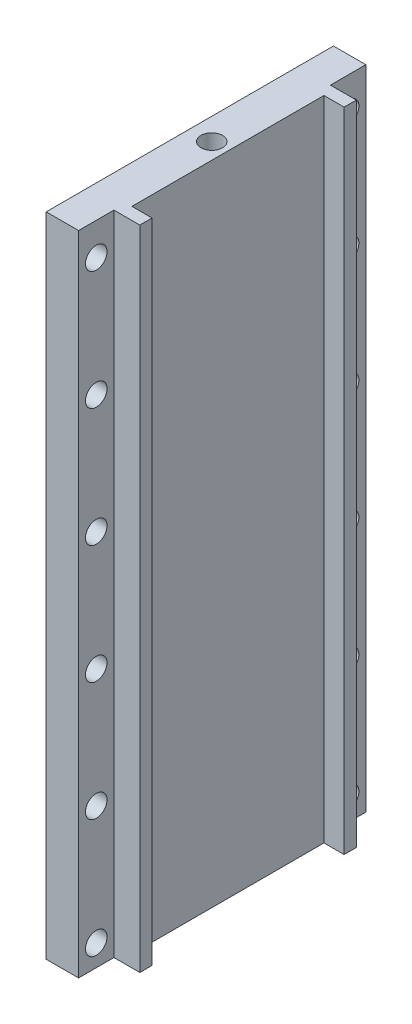
SolidWorks part; units mm, degrees
ref_plane "Front Plane" through (0, 0, 0) normal (0, 0, 1) x (1, 0, 0)
ref_plane "Top Plane" through (0, 0, 0) normal (0, 1, 0) x (1, 0, 0)
ref_plane "Right Plane" through (0, 0, 0) normal (1, 0, 0) x (0, 0, -1)
sketch "Sketch2" plane through (0, 0, 0) normal (0, 1, 0) x (1, 0, 0)
  line L0 (0, 0) -> (0, 133.12)
  line L1 (0, 133.12) -> (15, 133.12)
  line L2 (15, 133.12) -> (15, 116.725)
  line L3 (15, 116.725) -> (27, 116.725)
  line L4 (27, 116.725) -> (27, 111.06)
  line L5 (27, 111.06) -> (17.665, 111.06)
  line L6 (17.665, 111.06) -> (17.665, 22.06)
  line L7 (17.665, 22.06) -> (27, 22.06)
  line L8 (0, 0) -> (15, 0)
  line L9 (15, 0) -> (15, 16.395)
  line L10 (15, 16.395) -> (27, 16.395)
  line L11 (27, 16.395) -> (27, 22.06)
  dimension "D1" = 89
  dimension "D2" = 100.33
  dimension "D3" = 9.335
  dimension "D4" = 15
  dimension "D5" = 133.12
  dimension "D6" = 12
extrude "Boss-Extrude1" add sketch "Sketch2" along normal blind 300
sketch "Sketch3" plane through (15, 0, 0) normal (1, 0, 0) x (0, 0, -1)
  line L0 (0, 300) -> (16.395, 300) construction
  line L1 (16.395, 300) -> (116.725, 300) construction
  line L2 (66.56, 300) -> (66.56, 265.5045) construction
  circle A0 centre (8.1975, 285) radius 5
  circle A1 centre (8.1975, 230) radius 5
  circle A2 centre (8.1975, 175) radius 5
  circle A3 centre (8.1975, 120) radius 5
  circle A4 centre (8.1975, 65) radius 5
  circle A5 centre (8.1975, 10) radius 5
  circle A6 centre (124.9225, 10) radius 5
  circle A7 centre (124.9225, 65) radius 5
  circle A8 centre (124.9225, 120) radius 5
  circle A9 centre (124.9225, 175) radius 5
  circle A10 centre (124.9225, 230) radius 5
  circle A11 centre (124.9225, 285) radius 5
  point P4 (8.1975, 300)
  dimension "D1" = 10
  dimension "D2" = 15
  dimension "D3" = 6
extrude "Cut-Extrude1" cut sketch "Sketch3" against normal through all
sketch "Sketch5" plane through (0, 300, 0) normal (0, 1, 0) x (1, 0, 0)
  circle A0 centre (10.165, 66.5632) radius 5
extrude "Cut-Extrude2" cut sketch "Sketch5" against normal blind 10
sketch "Sketch7" plane through (0, 0, 0) normal (0, -1, 0) x (1, 0, 0)
  circle A0 centre (10.165, -66.56) radius 5
extrude "Cut-Extrude5" cut sketch "Sketch7" against normal blind 10
